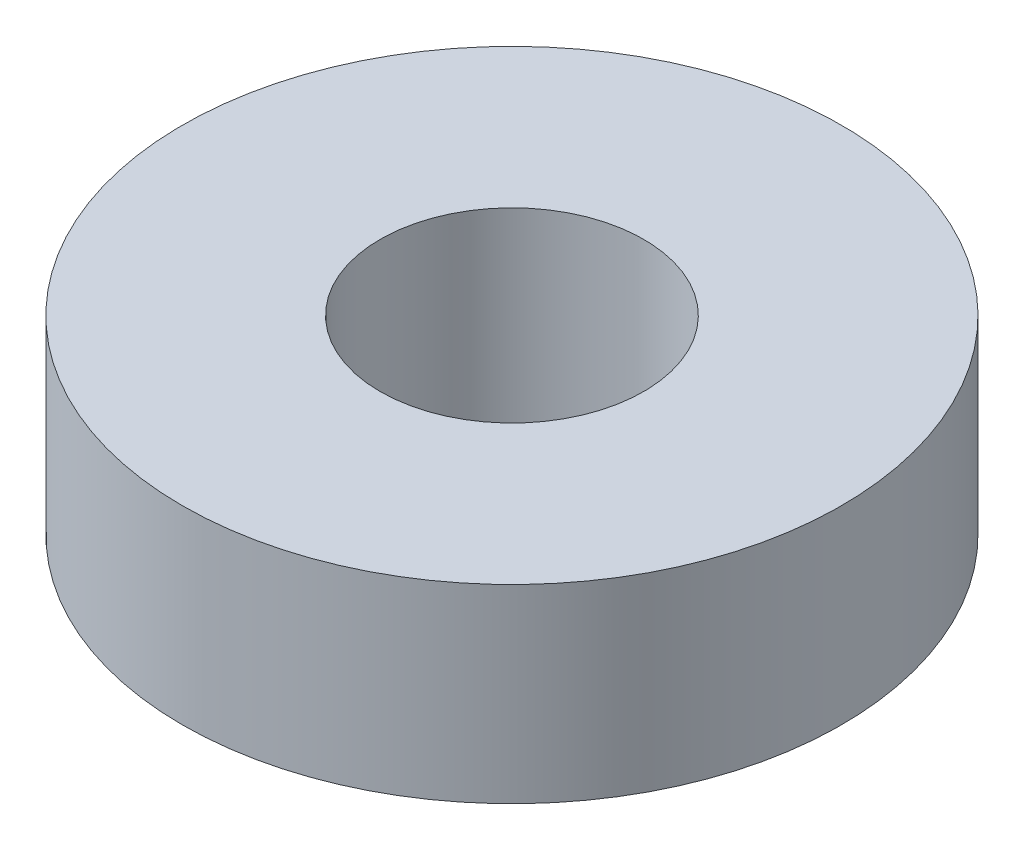
SolidWorks part; units mm, degrees
ref_plane "Front Plane" through (0, 0, 0) normal (0, 0, 1) x (1, 0, 0)
ref_plane "Top Plane" through (0, 0, 0) normal (0, 1, 0) x (1, 0, 0)
ref_plane "Right Plane" through (0, 0, 0) normal (1, 0, 0) x (0, 0, -1)
sketch "Sketch1" plane through (0, 0, 0) normal (0, 1, 0) x (1, 0, 0)
  circle A0 centre (0, 0) radius 6.35
  circle A1 centre (0, 0) radius 15.875
extrude "Boss-Extrude1" add sketch "Sketch1" along normal blind 9.144
